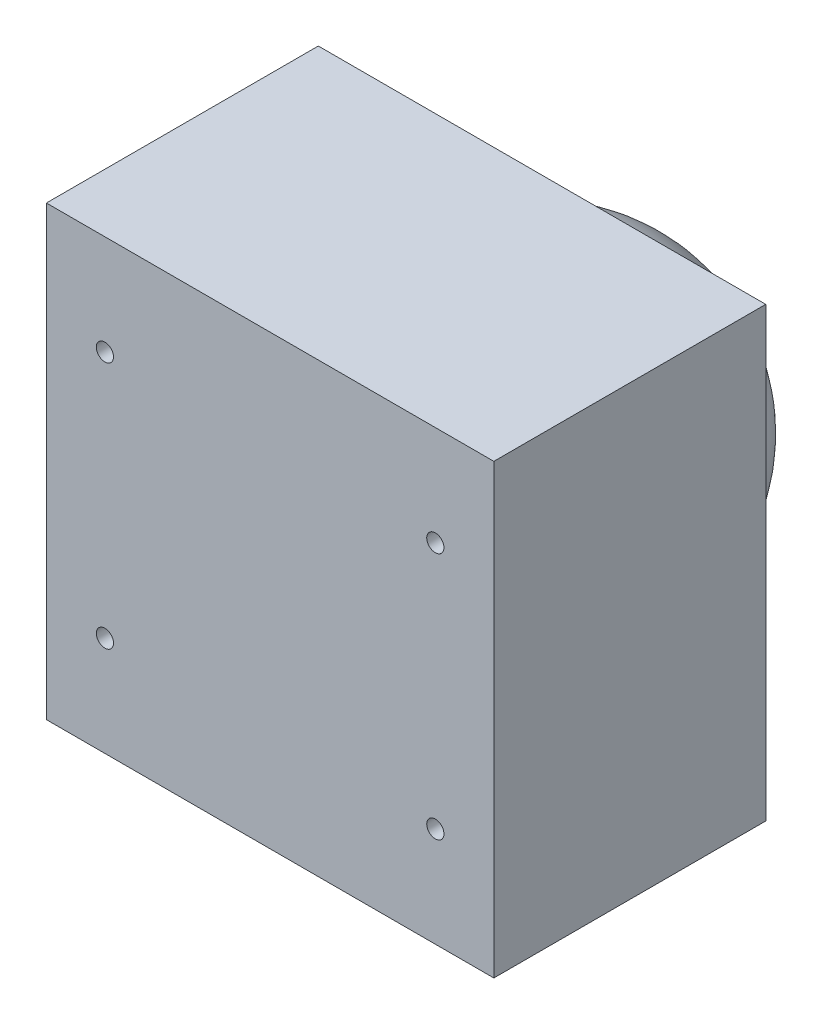
SolidWorks part; units mm, degrees
material "Acciaio al carbonio semplice"
ref_plane "Piano frontale" through (0, 0, 0) normal (0, 0, 1) x (1, 0, 0)
ref_plane "Piano superiore" through (0, 0, 0) normal (0, 1, 0) x (1, 0, 0)
ref_plane "Piano destro" through (0, 0, 0) normal (1, 0, 0) x (0, 0, -1)
sketch "Schizzo1" plane through (0, 0, 0) normal (0, 0, 1) x (1, 0, 0)
  line L1 (-32.5, 32.5) -> (32.5, 32.5)
  line L2 (-32.5, 32.5) -> (-32.5, -32.5)
  line L3 (-32.5, -32.5) -> (32.5, -32.5)
  line L4 (32.5, 32.5) -> (32.5, -32.5)
  line L5 (-32.5, 32.5) -> (32.5, -32.5) construction
  line L6 (-32.5, -32.5) -> (32.5, 32.5) construction
  point P0 (0, 0)
  dimension "D1" = 65
extrude "Estrusione-Estrusione1" add sketch "Schizzo1" along normal blind 39.5
ref_plane "Piano1" through (0, 0, -60.5) normal (0, 0, -1) x (-1, 0, 0)
ref_plane "Piano2" through (0, 0, -585.3) normal (0, 0, -1) x (-1, 0, 0)
ref_plane "Piano3" through (-202.66, 0, 0) normal (-1, 0, 0) x (0, 0, 1)
ref_plane "Piano4" through (0, -500, 0) normal (0, -1, 0) x (-1, 0, 0)
ref_plane "Piano7" through (0, 0, 139.5) normal (0, 0, 1) x (1, 0, 0)
ref_plane "Piano5" through (32.5, 0, 0) normal (1, 0, 0) x (0, 0, -1)
sketch "Schizzo2" plane through (0, 0, 0) normal (0, 1, 0) x (1, 0, 0)
  line L0 (0, 0) -> (0, 20.5)
  line L1 (0, 20.5) -> (12.48, 20.5)
  line L2 (0, 0) -> (24, 0)
  line L3 (32.5, 0) -> (-32.5, 0) construction
  line L5 (32.5, -39.5) -> (-32.5, -39.5) construction
  arc A0 (24, 0) -> (12.48, 20.5) centre (0, 0) ccw
  dimension "D1" = 60
  dimension "D2" = 24
revolve "Rivoluzione1" add sketch "Schizzo2" angle 360 about L0
sketch "Schizzo4" plane through (0, 0, 0) normal (0, 1, 0) x (1, 0, 0)
  line L0 (32.5, -39.5) -> (-32.5, -39.5) construction
  line L1 (0, -992.5) -> (0, 49007.5) construction
  point P0 (0, 7.5)
  dimension "D1" = 47
sketch "Schizzo13" plane through (0, 0, 0) normal (0, 1, 0) x (1, 0, 0)
  line L0 (0, 7.5) -> (451.4268, 585.3) construction
  line L1 (32.5, 0) -> (-32.5, 0) construction
  line L2 (35.75, 585.3) -> (-35.75, 585.3) construction
  dimension "D1" = 52
ref_point "Punto1"
sketch "Schizzo5" plane through (0, 0, 0) normal (0, 1, 0) x (1, 0, 0)
  line L2 (-999.5584, 7.5) -> (49000.4416, 7.5) construction
  line L3 (0, -992.5) -> (0, 49007.5) construction
  line L4 (20.1593, 33.3027) -> (2462.6459, 3159.543) construction
  line L5 (0, 7.5) -> (2462.6459, 3159.543) construction
  line L7 (0, 7.5) -> (3970.1846, -479.9774) construction
  line L8 (32.5, 3.5095) -> (3970.1846, -479.9774)
  line L11 (20.1593, 33.3027) -> (451.4268, 585.3)
  line L12 (451.4268, 585.3) -> (3958.0484, 585.3)
  line L13 (35.75, 585.3) -> (-35.75, 585.3) construction
  arc A0 (3970.1846, -479.9774) -> (2462.6459, 3159.543) centre (0, 7.5) ccw construction
  arc A1 (32.5, 3.5095) -> (20.1593, 33.3027) centre (0, 7.5) ccw
  arc A2 (3970.1846, -479.9774) -> (3958.0484, 585.3) centre (0, 7.5) ccw
  point P11 (4000, 7.5)
  dimension "D1" = 52
  dimension "D2" = 4000
  dimension "D4" = 7
sketch "Schizzo14" plane through (-32.5, 0, 0) normal (-1, 0, 0) x (0, 0, 1)
  line L0 (39.5, 32.5) -> (39.5, -32.5) construction
  circle A0 centre (25.2, 0) radius 6
  point P4 (0, 0)
  dimension "D2" = 12
  dimension "D1" = 14.3
extrude "Estrusione-Estrusione2" add sketch "Schizzo14" along normal blind 7
sketch "Schizzo15" plane through (0, 0, 39.5) normal (0, 0, 1) x (1, 0, 0)
  line L1 (-24, 18) -> (24, 18)
  line L2 (-24, 18) -> (-24, -18)
  line L3 (-24, -18) -> (24, -18)
  line L4 (24, 18) -> (24, -18)
  line L5 (-24, 18) -> (24, -18) construction
  line L6 (-24, -18) -> (24, 18) construction
  point P1 (0, 0)
  dimension "D1" = 48
  dimension "D2" = 36
hole_wizard "Foro filettato M3-1" positions "Schizzo3D1" profile "Schizzo16" tap size "M3" standard "ISO"
sketch3d "Schizzo3D1"
  point P0 (-24, 18, 39.5)
  point P3 (-24, -18, 39.5)
  point P6 (24, 18, 39.5)
  point P9 (24, -18, 39.5)
sketch "Schizzo16" plane through (-24, 18, 39.5) normal (1, 0, 0) x (0, -1, 0)
  line L0 (0, 0) -> (0, 5)
  line L1 (0, 5) -> (1.25, 4.2489)
  line L2 (1.25, 4.2489) -> (1.25, 0)
  line L5 (1.25, 0) -> (0, 0)
  line L10 (0, 5) -> (-1.25, 4.2489) construction
  line L11 (0, -6.35) -> (0, 107.95) construction
  dimension "Tap Drill Dia." = 2.5
  dimension "Tap Drill Depth" = 5
  dimension "Drill Angle" = 118
cosmetic thread "Filettatura del foro1" parameters "D1"=2, "D2"=3
cosmetic thread "Filettatura del foro2" parameters "D1"=2, "D2"=3
cosmetic thread "Filettatura del foro3" parameters "D1"=2, "D2"=3
cosmetic thread "Filettatura del foro4" parameters "D1"=2, "D2"=3
